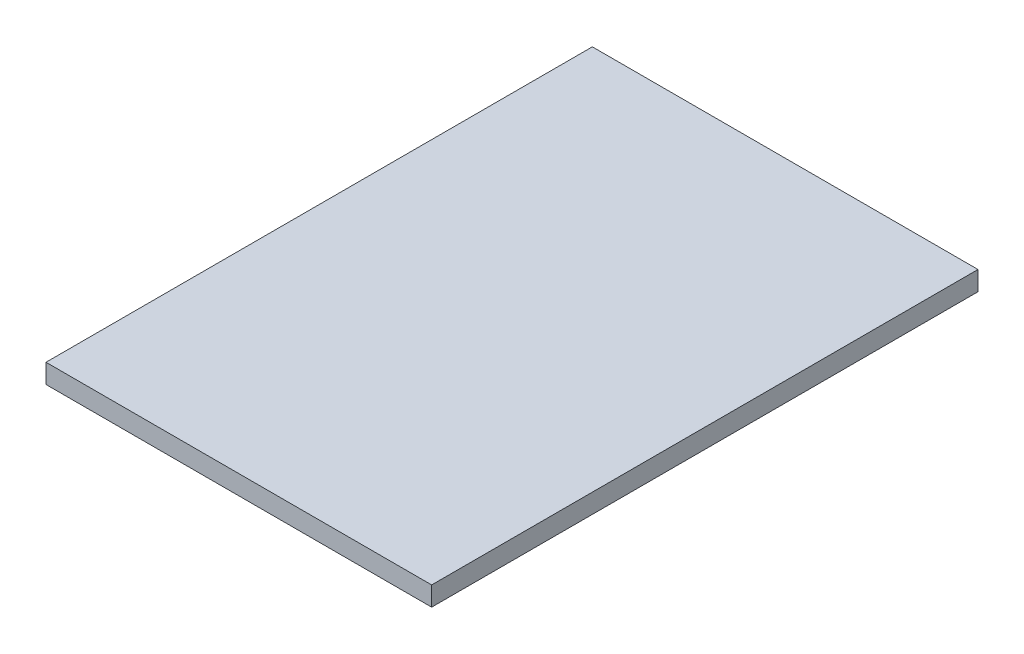
SolidWorks part; units mm, degrees
ref_plane "Спереди" through (0, 0, 0) normal (0, 0, 1) x (1, 0, 0)
ref_plane "Сверху" through (0, 0, 0) normal (0, 1, 0) x (1, 0, 0)
ref_plane "Справа" through (0, 0, 0) normal (1, 0, 0) x (0, 0, -1)
sketch "Эскиз1" plane through (0, 0, 0) normal (0, 1, 0) x (1, 0, 0)
  line L0 (64, 0) -> (4, 0)
  line L1 (64, 0) -> (64, -85)
  line L2 (4, 0) -> (4, -85)
  line L3 (4, -85) -> (64, -85)
extrude "Бобышка-Вытянуть1" add sketch "Эскиз1" along normal blind 3
